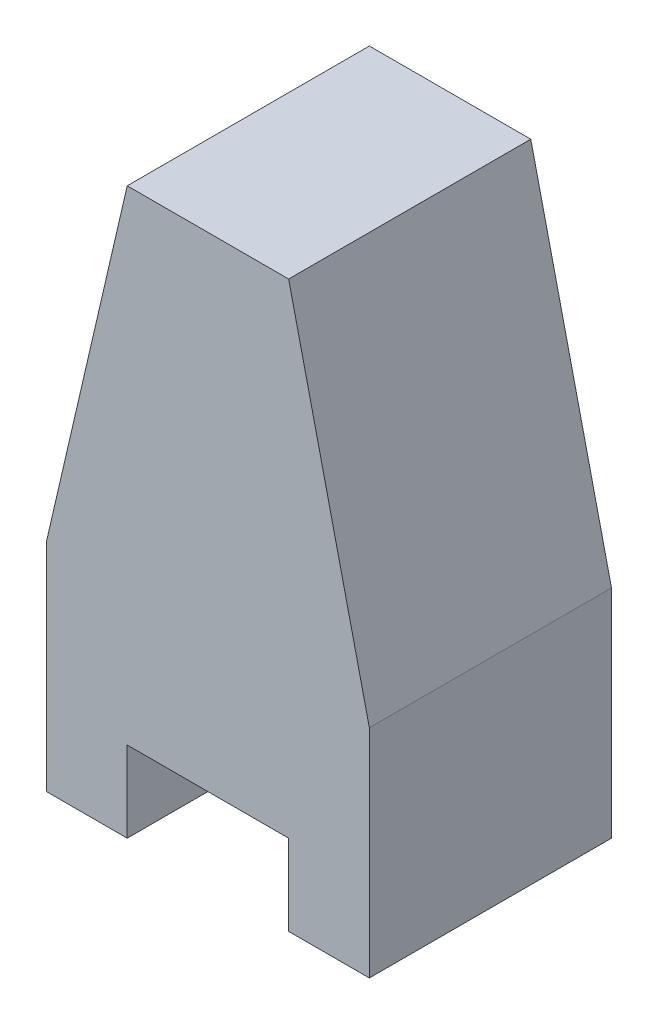
SolidWorks part; units mm, degrees
ref_plane "Front Plane" through (0, 0, 0) normal (0, 0, 1) x (1, 0, 0)
ref_plane "Top Plane" through (0, 0, 0) normal (0, 1, 0) x (1, 0, 0)
ref_plane "Right Plane" through (0, 0, 0) normal (1, 0, 0) x (0, 0, -1)
sketch "Sketch4" plane through (0, 0, 0) normal (0, 0, 1) x (1, 0, 0)
  line L0 (-20, -9.0734) -> (-15, 12.5)
  line L1 (-20, -22.5) -> (-15, -22.5)
  line L2 (-20, -22.5) -> (-20, -9.0734)
  line L3 (-15, 12.5) -> (-5, 12.5)
  line L4 (0, -22.5) -> (0, -9.0734)
  line L5 (-15, -17.5) -> (-5, -17.5)
  line L8 (-15, -22.5) -> (-15, -17.5)
  line L10 (-5, -22.5) -> (-5, -17.5)
  line L11 (0, -9.0734) -> (-5, 12.5)
  line L12 (-5, -22.5) -> (0, -22.5)
  point P0 (0, 0)
  dimension "D1" = 30
  dimension "D2" = 20
  dimension "D3" = 10
  dimension "D4" = 5
  dimension "D5" = 10
  dimension "D7" = 13.4266
  dimension "D8" = 5
  dimension "D9" = 5
extrude "Boss-Extrude1" add sketch "Sketch4" along normal blind 15
